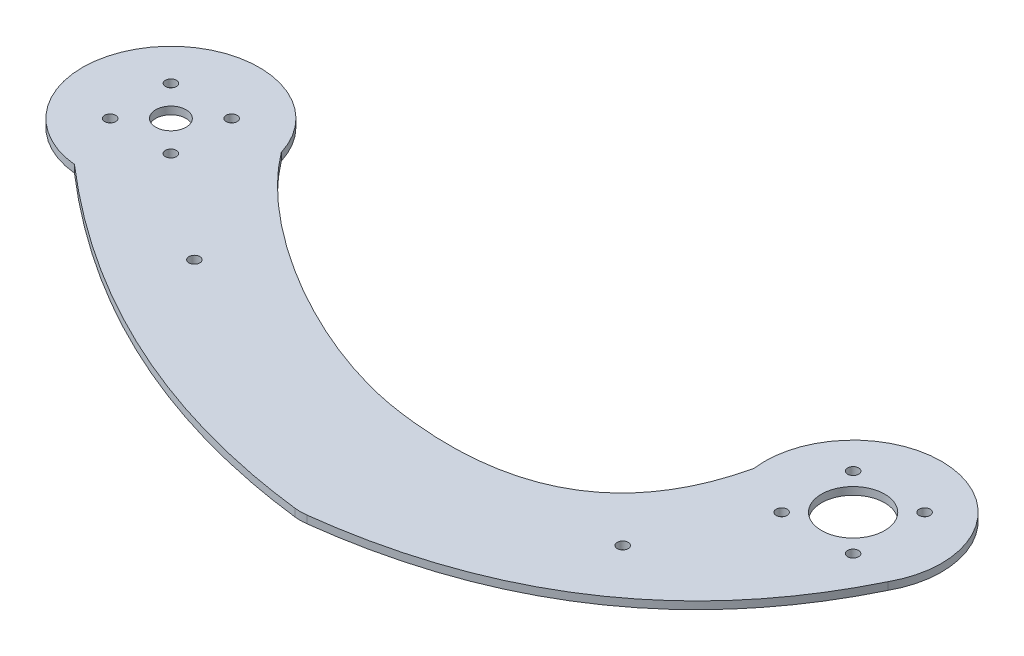
SolidWorks part; units mm, degrees
material "1060 Alloy"
ref_plane "Front" through (0, 0, 0) normal (0, 0, 1) x (1, 0, 0)
ref_plane "Top" through (0, 0, 0) normal (0, 1, 0) x (1, 0, 0)
ref_plane "Right" through (0, 0, 0) normal (1, 0, 0) x (0, 0, -1)
sketch "Sketch2" plane through (0, 0, 0) normal (0, 1, 0) x (1, 0, 0)
  line L0 (-66.9937, -19.8163) -> (-38.6545, -100.58) construction
  line L1 (-135, 0) -> (0, 0) construction
  line L2 (0, 17.5) -> (0, -17.5) construction
  line L3 (-17.5, 0) -> (17.5, 0) construction
  line L4 (-7.0711, 7.0711) -> (0, 0) construction
  line L5 (-67.5, 0) -> (-66.9937, 86.1749) construction
  line L6 (-135, 0) -> (-135, 17.5) construction
  line L7 (-135, 0) -> (-128.9896, 6.0104) construction
  arc A0 (15.331, -8.4387) -> (-17.3458, -2.3184) centre (0, 0) ccw
  arc A1 (-117.5, 0) -> (-136.6647, -17.4206) centre (-135, 0) ccw
  circle A2 centre (0, 0) radius 6.25
  circle A3 centre (-7.0711, 7.0711) radius 1.09
  circle A4 centre (-135, 0) radius 3
  circle A5 centre (7.0711, 7.0711) radius 1.09
  circle A6 centre (7.0711, -7.0711) radius 1.09
  circle A7 centre (-7.0711, -7.0711) radius 1.09
  circle A8 centre (-128.9896, 6.0104) radius 1.09
  circle A9 centre (-128.9896, -6.0104) radius 1.09
  circle A10 centre (-141.0104, -6.0104) radius 1.09
  circle A11 centre (-141.0104, 6.0104) radius 1.09
  spline S0 degree 2 poles (-17.3458, -2.3184) (-24.5723, -34.0048) (-64.3721, -27.2877) knots 0 0 0 1 1 1
  spline S1 degree 2 poles (15.331, -8.4387) (-4.3287, -48.9171) (-54.7702, -54.652) knots 0 0 0 1 1 1
  spline S2 degree 3 poles (-118.2611, 5.1047) (-107.6552, -9.0242) (-84.0425, -23.6719) (-64.3721, -27.2877) knots 0 0 0 0 1 1 1 1
  spline S3 degree 2 poles (-136.6647, -17.4206) (-99.493, -49.6651) (-54.7702, -54.652) knots 0 0 0 1 1 1
  point P32 (0, 0)
  point P41 (-135, 0)
  dimension "D1" = 35
  dimension "D2" = 35
  dimension "D4" = 90
  dimension "D5" = 53
  dimension "D6" = 60
  dimension "D7" = 90
  dimension "D9" = 65
  dimension "D10" = 2.18
  dimension "D13" = 12.5
  dimension "D15" = 6
  dimension "D16" = 2.18
  dimension "D3" = 135
  dimension "D8" = 29
  dimension "D11" = 10
  dimension "D12" = 45
  dimension "D17" = 8.5
  dimension "D18" = 45
  dimension "D14" = 4
  dimension "D19" = 4
extrude "Boss-Extrude1" add sketch "Sketch2" along normal blind 1.5
fillet "Fillet1" radius 10 1 edges at (-54.7702, 0.75, 54.652)
ref_plane "Plane1" through (0, 1.5, 0) normal (0, 1, 0) x (1, 0, 0)
sketch "Sketch3" plane through (0, 1.5, 0) normal (0, 1, 0) x (1, 0, 0)
  line L0 (-25.9556, -19.3545) -> (-8.2771, -37.5959) construction
  line L2 (-101.7375, -10.399) -> (-115.1862, -33.3846) construction
  circle A0 centre (-17.1163, -28.4752) radius 1.09
  circle A2 centre (-108.4618, -21.8918) radius 1.09
  parabola Q2 (-136.6647, -17.4206) -> (-55.974, -54.5127) focus (-58.2165, 16.8599) apex (-76.8501, -50.4023) construction
  parabola Q4 (15.331, -8.4387) -> (-53.5631, -54.5092) focus (-28.2198, -5.8892) apex (-3.5461, -33.7383) construction
  parabola Q5 (-17.3458, -2.3184) -> (-64.3721, -27.2877) focus (-36.5074, -10.8501) apex (-27.8192, -21.0934) construction
  spline S0 degree 3 poles (-118.2611, 5.1047) (-107.6552, -9.0242) (-84.0425, -23.6719) (-64.3721, -27.2877) knots 0 0 0 0 1 1 1 1 construction
  point P0 (-25.9556, -19.3545)
  point P1 (-8.2771, -37.5959)
  point P15 (-101.7375, -10.399)
  point P16 (-115.1862, -33.3846)
  dimension "D1" = 2.18
extrude "Cut-Extrude1" cut sketch "Sketch3" against normal blind 10
